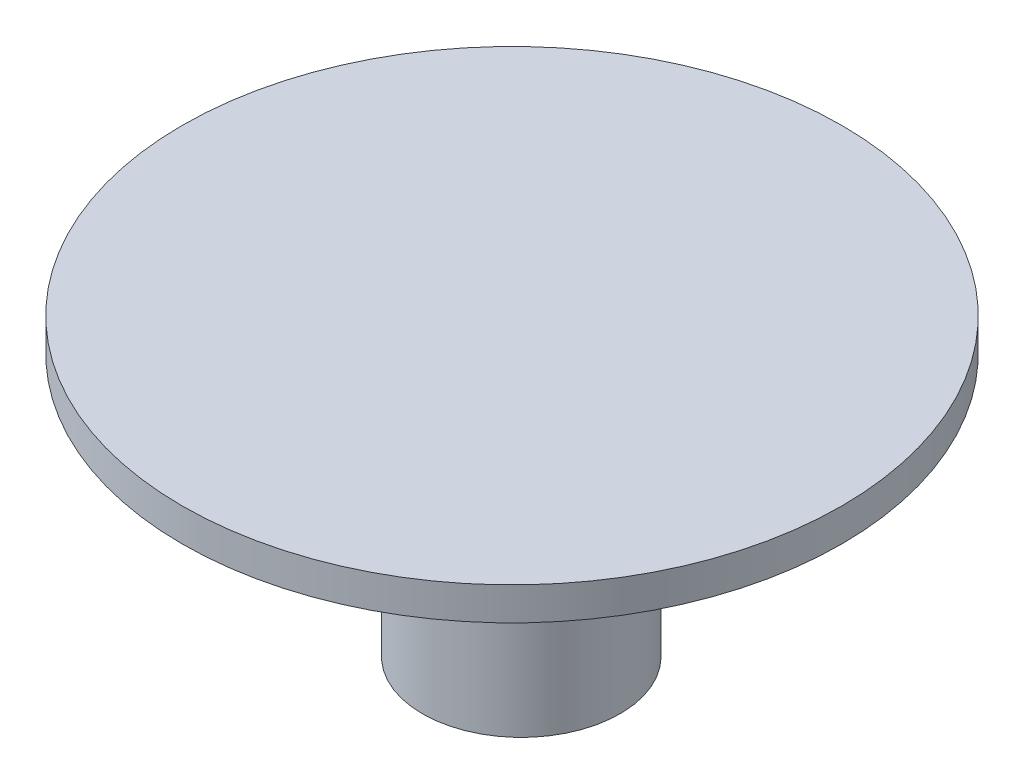
SolidWorks part; units mm, degrees
ref_plane "Front Plane" through (0, 0, 0) normal (0, 0, 1) x (1, 0, 0)
ref_plane "Top Plane" through (0, 0, 0) normal (0, 1, 0) x (1, 0, 0)
ref_plane "Right Plane" through (0, 0, 0) normal (1, 0, 0) x (0, 0, -1)
sketch "Sketch1" plane through (0, 0, 0) normal (0, 1, 0) x (1, 0, 0)
  circle A0 centre (-4.4166, 7.1435) radius 3
  point P2 (0, 0)
  point P3 (0, 0)
  point P4 (0, 0)
  point P5 (-4.4166, 7.1435)
  point P6 (0, 0)
extrude "Boss-Extrude1" add sketch "Sketch1" along normal blind 8 contours A0
sketch "Sketch2" plane through (0, 8, 0) normal (0, 1, 0) x (1, 0, 0)
  circle A0 centre (-4.5219, 6.9677) radius 10.0064
  point P2 (0, 0)
  point P3 (0, 0)
extrude "Boss-Extrude2" add sketch "Sketch2" along normal blind 1
